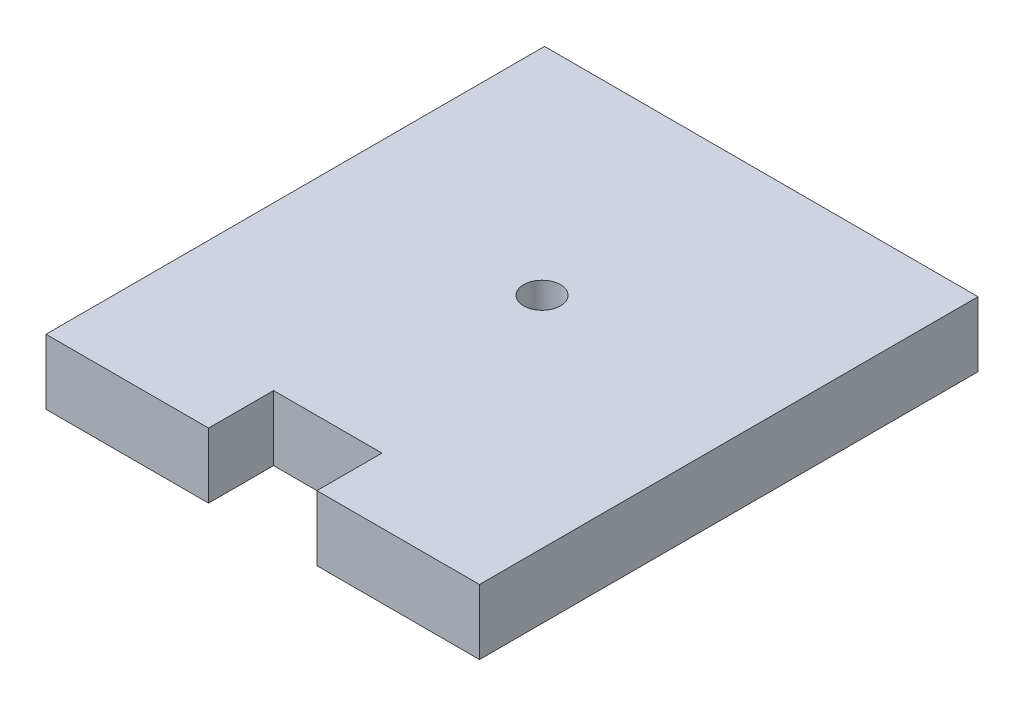
SolidWorks part; units mm, degrees
ref_plane "Front" through (0, 0, 0) normal (0, 0, 1) x (1, 0, 0)
ref_plane "Top" through (0, 0, 0) normal (0, 1, 0) x (1, 0, 0)
ref_plane "Right" through (0, 0, 0) normal (1, 0, 0) x (0, 0, -1)
sketch "Sketch1" plane through (0, 0, 0) normal (0, 1, 0) x (1, 0, 0)
  line L1 (0, 0) -> (20, 0)
  line L2 (0, 0) -> (0, -23)
  line L3 (0, -23) -> (20, -23)
  line L4 (20, 0) -> (20, -23)
  circle A0 centre (9.8868, -9.9994) radius 0.85
  point P7 (0, 0)
  point P8 (9.887, -9.4251)
  point P9 (10, 0)
  point P10 (0, -11.5)
  dimension "D3" = 1.7
  dimension "D5" = 10
  dimension "D1" = 20
  dimension "D2" = 23
  dimension "D4" = 10
extrude "Boss-Extrude1" add sketch "Sketch1" along normal blind 3
sketch "Sketch3" plane through (0, 3, 0) normal (0, 1, 0) x (1, 0, 0)
  line L0 (0, -23) -> (20, -23) construction
  line L1 (7.5, -20) -> (12.5, -20)
  line L2 (7.5, -20) -> (7.5, -23)
  line L3 (7.5, -23) -> (12.5, -23)
  line L4 (12.5, -20) -> (12.5, -23)
  line L5 (0, 0) -> (0, -23) construction
  dimension "D1" = 3
  dimension "D2" = 5
  dimension "D3" = 7.5
extrude "Cut-Extrude1" cut sketch "Sketch3" against normal through all
